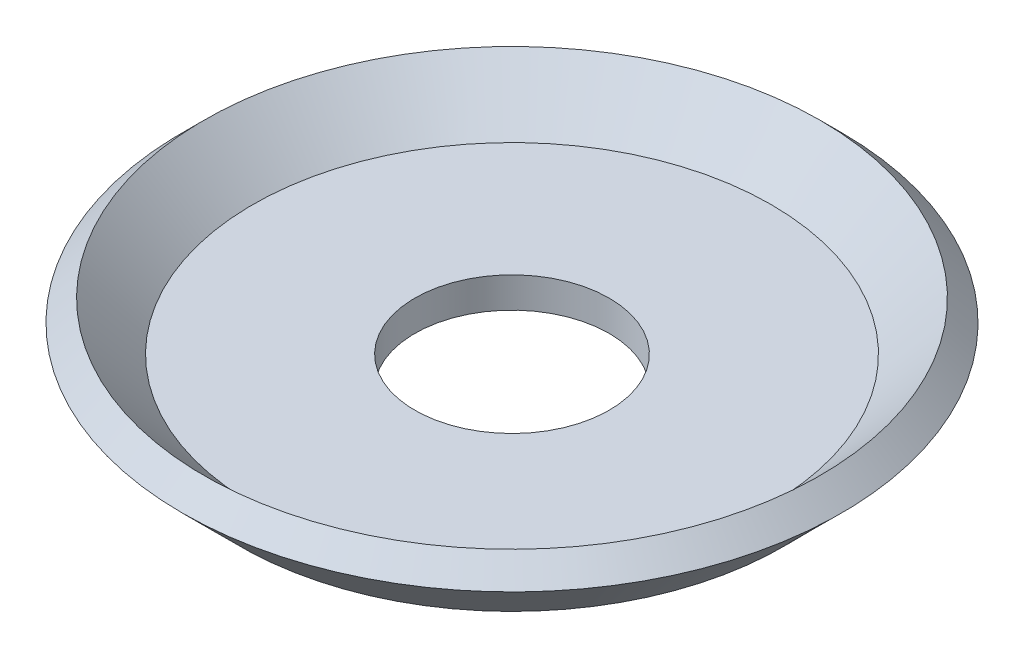
SolidWorks part; units mm, degrees
ref_plane "Front Plane" through (0, 0, 0) normal (0, 0, 1) x (1, 0, 0)
ref_plane "Top Plane" through (0, 0, 0) normal (0, 1, 0) x (1, 0, 0)
ref_plane "Right Plane" through (0, 0, 0) normal (1, 0, 0) x (0, 0, -1)
sketch "Sketch1" plane through (0, 0, 0) normal (1, 0, 0) x (0, 0, -1)
  line L0 (0, 0) -> (0, 15.7358) construction
  line L1 (-4.7625, 0) -> (-13.3213, 0)
  line L2 (-13.3213, 0) -> (-16.1497, 2.8284)
  line L3 (-16.1497, 2.8284) -> (-15.0891, 3.8891)
  line L4 (-15.0891, 3.8891) -> (-12.7, 1.5)
  line L5 (-12.7, 1.5) -> (-4.7625, 1.5)
  line L7 (-4.7625, 0) -> (-4.7625, 1.5)
  point P8 (0, 0)
  dimension "D1" = 1.5
  dimension "D2" = 1.5
  dimension "D3" = 135
  dimension "D4" = 4
  dimension "D5" = 25.4
  dimension "D6" = 9.525
revolve "Revolve1" add sketch "Sketch1" angle 360 about L0
